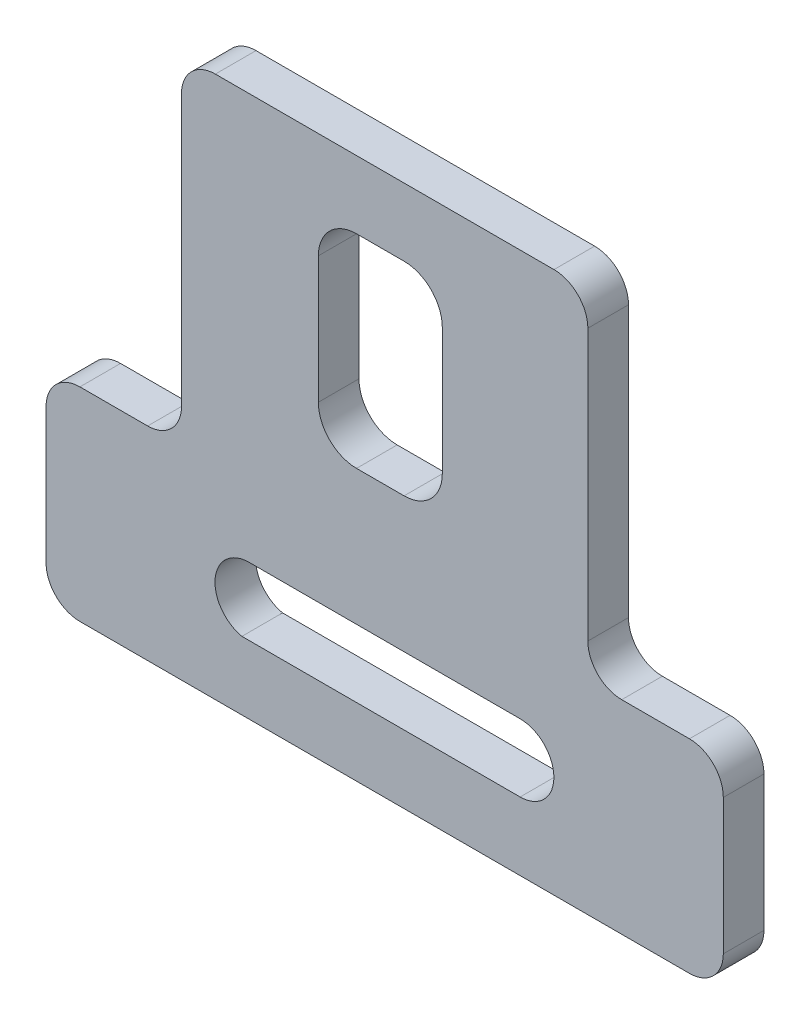
SolidWorks part; units mm, degrees
ref_plane "Front Plane" through (0, 0, 0) normal (0, 0, 1) x (1, 0, 0)
ref_plane "Top Plane" through (0, 0, 0) normal (0, 1, 0) x (1, 0, 0)
ref_plane "Right Plane" through (0, 0, 0) normal (1, 0, 0) x (0, 0, -1)
sketch "Sketch1" plane through (0, 0, 0) normal (0, 0, 1) x (1, 0, 0)
  line L0 (-175, -125) -> (-225, -125)
  line L2 (-150, -100) -> (-150, 100)
  line L3 (-125, 125) -> (125, 125)
  line L4 (150, -100) -> (150, 100)
  line L5 (-150, -125) -> (150, 125) construction
  line L6 (-150, 125) -> (150, -125) construction
  line L7 (225, -275) -> (-225, -275)
  line L8 (250, -250) -> (250, -150)
  line L9 (225, -125) -> (175, -125)
  line L10 (-250, -250) -> (-250, -150)
  line L11 (250, -275) -> (-250, -125) construction
  line L12 (250, -125) -> (-250, -275) construction
  line L14 (-20.7859, 75) -> (14.3361, 75)
  line L15 (-48.975, 46.8109) -> (-48.975, -46.8109)
  line L16 (-20.7859, -75) -> (14.3361, -75)
  line L17 (42.5252, 46.8109) -> (42.5252, -46.8109)
  line L18 (-100.1641, -174.7074) -> (99.8359, -174.7074)
  line L20 (-105.4129, -224.7071) -> (99.999, -224.7071)
  arc A0 (14.3361, -75) -> (42.5252, -46.8109) centre (14.3361, -46.8109) ccw
  arc A1 (-20.7859, -75) -> (-48.975, -46.8109) centre (-20.7859, -46.8109) cw
  arc A2 (42.5252, 46.8109) -> (14.3361, 75) centre (14.3361, 46.8109) ccw
  arc A3 (-48.975, 46.8109) -> (-20.7859, 75) centre (-20.7859, 46.8109) cw
  arc A6 (-100.1641, -174.7074) -> (-105.4129, -224.7071) centre (-100, -200) ccw
  arc A7 (99.999, -224.7071) -> (99.8359, -174.7074) centre (99.9175, -199.7073) ccw
  arc A8 (-125, 125) -> (-150, 100) centre (-125, 100) ccw
  arc A9 (150, 100) -> (125, 125) centre (125, 100) ccw
  arc A10 (225, -275) -> (250, -250) centre (225, -250) ccw
  arc A11 (250, -150) -> (225, -125) centre (225, -150) ccw
  arc A12 (-225, -275) -> (-250, -250) centre (-225, -250) cw
  arc A13 (-250, -150) -> (-225, -125) centre (-225, -150) cw
  arc A14 (-150, -100) -> (-175, -125) centre (-175, -100) cw
  arc A15 (150, -100) -> (175, -125) centre (175, -100) ccw
  point P0 (0, 0)
  point P6 (0, -200)
  point P17 (42.5252, -75)
  point P22 (42.5252, 75)
  dimension "D7" = 28.1891
  dimension "D11" = 75
  dimension "D12" = 25
  dimension "D14" = 25
  dimension "D15" = 25
  dimension "D1" = 500
  dimension "D2" = 300
  dimension "D3" = 400
  dimension "D4" = 400
  dimension "D5" = 150
  dimension "D6" = 200
  dimension "D8" = 200
  dimension "D9" = 50
  dimension "D10" = 150
  dimension "D13" = 150
extrude "Boss-Extrude1" add sketch "Sketch1" along normal blind 30
